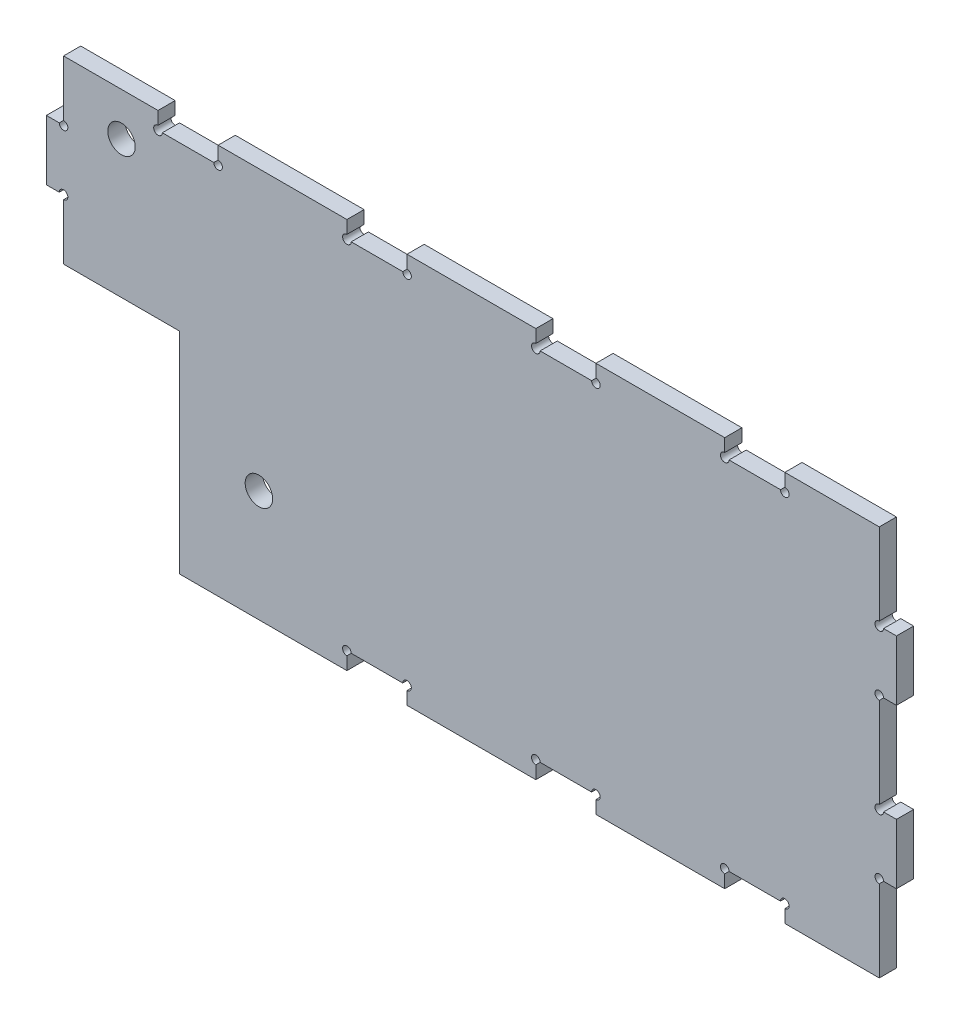
SolidWorks part; units mm, degrees
ref_plane "Front" through (0, 0, 0) normal (0, 0, 1) x (1, 0, 0)
ref_plane "Top" through (0, 0, 0) normal (0, 1, 0) x (1, 0, 0)
ref_plane "Right" through (0, 0, 0) normal (1, 0, 0) x (0, 0, -1)
sketch "草图1" plane through (0, 0, 0) normal (0, 0, 1) x (1, 0, 0)
  line L1 (0, 0) -> (95, 0)
  line L2 (0, 0) -> (0, 45.5)
  line L3 (0, 45.5) -> (95, 45.5)
  line L4 (95, 0) -> (95, 45.5)
  dimension "D1" = 95
  dimension "D2" = 45.5
extrude "凸台-拉伸1" add sketch "草图1" along normal blind 2
sketch "草图2" plane through (0, 0, 2) normal (0, 0, 1) x (1, 0, 0)
  line L0 (95, 45.5) -> (0, 45.5) construction
  line L1 (55, 45.5) -> (62, 45.5)
  line L2 (55, 45.5) -> (55, 43.5)
  line L3 (55, 43.5) -> (62, 43.5)
  line L4 (62, 45.5) -> (62, 43.5)
  line L5 (95, 0) -> (95, 45.5) construction
  line L6 (33, 45.5) -> (40, 45.5)
  line L7 (33, 45.5) -> (33, 43.5)
  line L8 (33, 43.5) -> (40, 43.5)
  line L9 (40, 45.5) -> (40, 43.5)
  line L10 (11, 45.5) -> (18, 45.5)
  line L11 (11, 45.5) -> (11, 43.5)
  line L12 (11, 43.5) -> (18, 43.5)
  line L13 (18, 45.5) -> (18, 43.5)
  line L14 (77, 45.5) -> (84, 45.5)
  line L15 (77, 45.5) -> (77, 43.5)
  line L16 (77, 43.5) -> (84, 43.5)
  line L17 (84, 45.5) -> (84, 43.5)
  line L19 (0, 0) -> (95, 0) construction
  line L25 (33, 0) -> (40, 0)
  line L26 (33, 0) -> (33, 2)
  line L27 (33, 2) -> (40, 2)
  line L28 (40, 0) -> (40, 2)
  line L29 (55, 0) -> (62, 0)
  line L30 (55, 0) -> (55, 2)
  line L31 (55, 2) -> (62, 2)
  line L32 (62, 0) -> (62, 2)
  line L33 (77, 0) -> (84, 0)
  line L34 (77, 0) -> (77, 2)
  line L35 (77, 2) -> (84, 2)
  line L36 (84, 0) -> (84, 2)
  dimension "D1" = 2
  dimension "D2" = 7
  dimension "D3" = 7
  dimension "D4" = 2
  dimension "D5" = 2
  dimension "D6" = 7
  dimension "D7" = 15
  dimension "D8" = 15
  dimension "D9" = 2
  dimension "D10" = 7
  dimension "D11" = 15
  dimension "D12" = 11
  dimension "D14" = 2
  dimension "D15" = 2
  dimension "D16" = 2
extrude "切除-拉伸1" cut sketch "草图2" against normal through all
sketch "草图3" plane through (0, 0, 2) normal (0, 0, 1) x (1, 0, 0)
  circle A0 centre (11, 43.5) radius 0.5
extrude "切除-拉伸2" cut sketch "草图3" against normal through all
sketch "草图5" plane through (0, 0, 2) normal (0, 0, 1) x (1, 0, 0)
  line L0 (0, 45.5) -> (0, 0) construction
  line L1 (0, 24.5) -> (13.5, 24.5)
  line L2 (0, 24.5) -> (0, 0)
  line L3 (0, 0) -> (13.5, 0)
  line L4 (13.5, 24.5) -> (13.5, 0)
  line L5 (0, 0) -> (33, 0) construction
  line L6 (11, 45.5) -> (0, 45.5) construction
  dimension "D1" = 21
  dimension "D2" = 13.5
extrude "切除-拉伸3" cut sketch "草图5" against normal through all
sketch "草图6" plane through (0, 0, 2) normal (0, 0, 1) x (1, 0, 0)
  line L0 (0, 45.5) -> (0, 24.5) construction
  line L1 (0, 38.5) -> (-2, 38.5)
  line L2 (0, 38.5) -> (0, 31.5)
  line L3 (0, 31.5) -> (-2, 31.5)
  line L4 (-2, 38.5) -> (-2, 31.5)
  line L5 (11, 45.5) -> (0, 45.5) construction
  line L7 (95, 0) -> (95, 45.5) construction
  line L8 (95, 35.5) -> (97, 35.5)
  line L9 (95, 35.5) -> (95, 28.5)
  line L10 (95, 28.5) -> (97, 28.5)
  line L11 (97, 35.5) -> (97, 28.5)
  line L12 (84, 0) -> (95, 0) construction
  line L13 (95, 17) -> (97, 17)
  line L14 (95, 17) -> (95, 10)
  line L15 (95, 10) -> (97, 10)
  line L16 (97, 17) -> (97, 10)
  line L17 (95, 45.5) -> (84, 45.5) construction
  dimension "D1" = 7
  dimension "D2" = 2
  dimension "D3" = 7
  dimension "D4" = 7
  dimension "D5" = 2
  dimension "D6" = 2
  dimension "D7" = 7
  dimension "D8" = 10
  dimension "D9" = 10
extrude "凸台-拉伸2" add sketch "草图6" against normal blind 2
sketch "草图4" plane through (0, 0, 2) normal (0, 0, 1) x (1, 0, 0)
  point P0 (18, 43.5)
  point P1 (33, 43.5)
  point P3 (40, 43.5)
  point P5 (55, 43.5)
  point P7 (62, 43.5)
  point P9 (77, 43.5)
  point P11 (84, 43.5)
  point P13 (84, 2)
  point P15 (77, 2)
  point P17 (62, 2)
  point P19 (55, 2)
  point P21 (40, 2)
  point P23 (33, 2)
  point P29 (0, 31.5)
  point P31 (95, 35.5)
  point P32 (0, 38.5)
  point P33 (95, 28.5)
  point P37 (95, 17)
  point P39 (95, 10)
pattern_sketch "草图阵列1" of "切除-拉伸2" driven by "草图4"
sketch "草图7" plane through (0, 0, 2) normal (0, 0, 1) x (1, 0, 0)
  circle A0 centre (6.75, 40.5) radius 1.6
  circle A1 centre (22.75, 13) radius 1.6
extrude "切除-拉伸4" cut sketch "草图7" against normal blind 2
